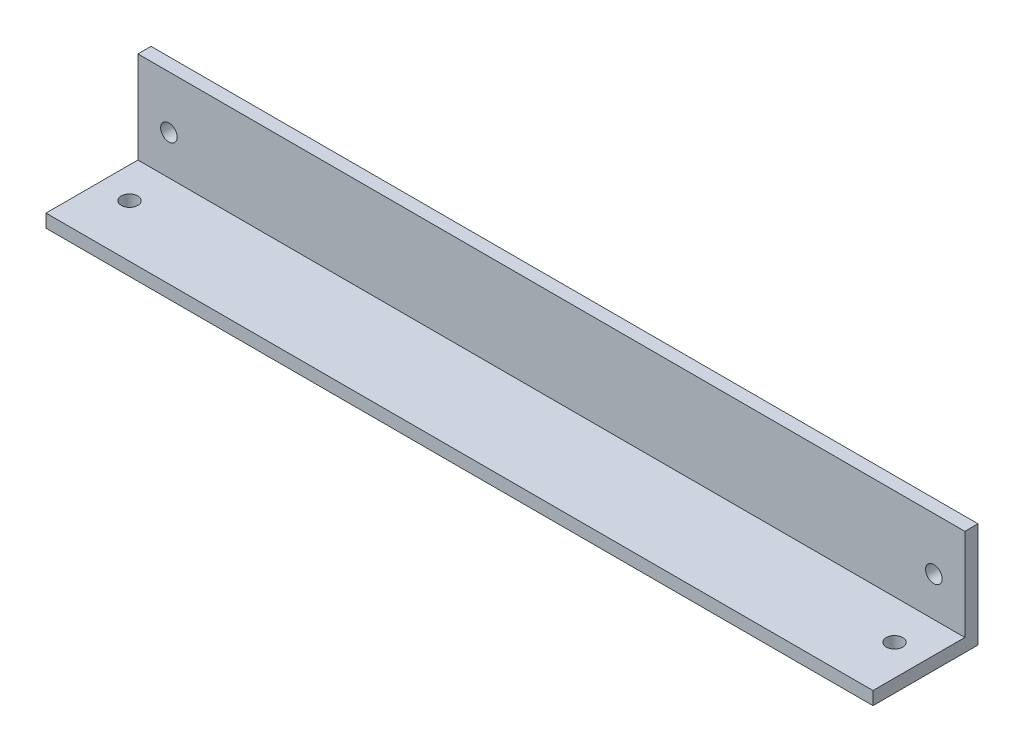
SolidWorks part; units mm, degrees
ref_plane "Front Plane" through (0, 0, 0) normal (0, 0, 1) x (1, 0, 0)
ref_plane "Top Plane" through (0, 0, 0) normal (0, 1, 0) x (1, 0, 0)
ref_plane "Right Plane" through (0, 0, 0) normal (1, 0, 0) x (0, 0, -1)
sketch "Sketch1" plane through (0, 0, 0) normal (1, 0, 0) x (0, 0, -1)
  line L0 (0, 50.8) -> (0, 0)
  line L1 (0, 0) -> (-50.8, 0)
  line L2 (-50.8, 0) -> (-50.8, 6.35)
  line L3 (-50.8, 6.35) -> (-6.35, 6.35)
  line L4 (-6.35, 6.35) -> (-6.35, 50.8)
  line L5 (-6.35, 50.8) -> (0, 50.8)
  dimension "D1" = 50.8
  dimension "D2" = 6.35
  dimension "D3" = 50.8
extrude "Boss-Extrude1" add sketch "Sketch1" along normal mid plane 400
sketch "Sketch2" plane through (0, 0, 0) normal (0, -1, 0) x (1, 0, 0)
  line L0 (-200, 25.4) -> (200, 25.4) construction
  line L1 (-200, 50.8) -> (-200, 0) construction
  line L2 (200, 50.8) -> (200, 0) construction
  line L3 (0, 50.8) -> (0, 0) construction
  line L4 (200, 50.8) -> (-200, 50.8) construction
  circle A0 centre (-185, 25.4) radius 4
  circle A1 centre (185, 25.4) radius 4
  dimension "D1" = 8
  dimension "D2" = 15
extrude "Cut-Extrude1" cut sketch "Sketch2" against normal up to next
ref_plane "Plane1" through (0, 0, 0) normal (0, -0.7071, 0.7071) x (-1, 0, 0)
mirror "Mirror1" about plane through (0, 0, 0) normal (0, -0.7071, 0.7071) of "Cut-Extrude1"
